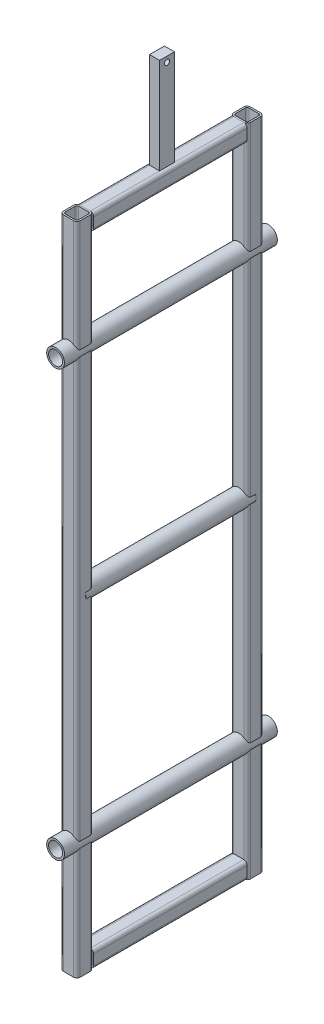
SolidWorks part; units mm, degrees
ref_plane "Front Plane" through (0, 0, 0) normal (1, 0, 0) x (0, 1, 0)
ref_plane "Top Plane" through (0, 0, 0) normal (0, 0, 1) x (0, 1, 0)
ref_plane "Right Plane" through (0, 0, 0) normal (0, 1, 0) x (-1, 0, 0)
sketch "Sketch1" plane through (0, 0, 0) normal (1, 0, 0) x (0, 1, 0)
  line L0 (-254, 254) -> (-254, -254) construction
  line L1 (-482.6, 254) -> (482.6, 254) construction
  line L2 (-482.6, 254) -> (-482.6, -254) construction
  line L3 (-482.6, -254) -> (482.6, -254) construction
  line L4 (482.6, 254) -> (482.6, -254) construction
  line L5 (-482.6, 254) -> (482.6, -254) construction
  line L6 (-482.6, -254) -> (482.6, 254) construction
  line L11 (-254, 133.6842) -> (254, -133.6842) construction
  line L13 (254, 254) -> (254, -254) construction
  point P0 (0, 0)
  point P6 (0, 0)
  dimension "D1" = 965.2
  dimension "D2" = 508
  dimension "D3" = 254
  dimension "D4" = 508
sketch3d "3DSketch1"
  line L7 (0, 0, 101.6) -> (0, 0, -101.6)
  line L8 (0, -381, 101.6) -> (0, 381, 101.6)
  line L9 (0, -254, 127) -> (0, -254, -127)
  line L10 (0, -254, 254) -> (0, -254, -254) construction
  line L11 (0, -381, 101.6) -> (0, -381, -101.6)
  line L12 (0, -381, -101.6) -> (0, 381, -101.6)
  line L13 (0, 381, 101.6) -> (0, 381, -101.6)
  line L14 (0, -381, 101.6) -> (0, 381, -101.6) construction
  line L15 (0, -381, -101.6) -> (0, 381, 101.6) construction
  line L16 (0, 254, 127) -> (0, 254, -127)
  line L17 (0, 254, 254) -> (0, 254, -254) construction
  point P0 (0, 0, 0)
  point P8 (0, 0, 0)
  dimension "D1" = 25.4
  dimension "D3" = 25.4
  dimension "D2" = 762
  dimension "D4" = 25.4
  dimension "D5" = 25.4
  dimension "D6" = 203.2
ref_plane "Plane2" through (0, -381, 101.6) normal (0, 0, -1) x (1, 0, 0)
ref_plane "Plane4" through (0, -381, 101.6) normal (0, 1, 0) x (1, 0, 0)
ref_plane "Plane5" through (0, -381, 101.6) normal (0, 0, -1) x (1, 0, 0)
ref_plane "Plane6" through (0, -381, 101.6) normal (0, 0, -1) x (1, 0, 0)
ref_plane "Plane7" through (0, -381, -101.6) normal (0, 1, 0) x (1, 0, 0)
ref_plane "Plane8" through (0, -381, 101.6) normal (0, 0, -1) x (1, 0, 0)
ref_plane "Plane9" through (0, -381, 101.6) normal (0, 0, -1) x (1, 0, 0)
ref_plane "Plane10" through (0, -381, 101.6) normal (0, 0, -1) x (1, 0, 0)
ref_plane "Plane11" through (0, -381, -101.6) normal (0, 1, 0) x (1, 0, 0)
ref_plane "Plane12" through (0, -381, 101.6) normal (0, 0, -1) x (1, 0, 0)
other "Pipe 21.3 X 2.3(1)"
ref_plane "Plane15" through (0, 0, 101.6) normal (0, 0, -1) x (1, 0, 0)
sketch "Sketch136" plane through (0, 0, 101.6) normal (0, 0, -1) x (1, 0, 0)
  circle A0 centre (0, 0) radius 8.35
  circle A1 centre (0, 0) radius 10.65
  point P3 (0, 10.65)
  point P5 (-10.65, 0)
  point P6 (0, -10.65)
  point P7 (10.65, 0)
  point P8 (0, 0)
  dimension "In_dia" = 16.7
  dimension "Out_dia" = 21.3
other "Square tube 20 X 20 X 2(7)"
ref_plane "Plane17" through (0, -381, -101.6) normal (0, 1, 0) x (1, 0, 0)
sketch "Sketch141" plane through (0, -381, -101.6) normal (0, 1, 0) x (1, 0, 0)
  line L0 (-6, -8) -> (6, -8)
  line L1 (-8, -6) -> (-8, 6)
  line L2 (6, 8) -> (-6, 8)
  line L3 (8, 6) -> (8, -6)
  line L4 (-6, -10) -> (6, -10)
  line L5 (-10, -6) -> (-10, 6)
  line L6 (6, 10) -> (-6, 10)
  line L7 (10, 6) -> (10, -6)
  arc A0 (10, 6) -> (6, 10) centre (6, 6) ccw
  arc A1 (6, -10) -> (10, -6) centre (6, -6) ccw
  arc A2 (-10, -6) -> (-6, -10) centre (-6, -6) ccw
  arc A3 (-6, 10) -> (-10, 6) centre (-6, 6) ccw
  arc A4 (-6, 8) -> (-8, 6) centre (-6, 6) ccw
  arc A5 (8, 6) -> (6, 8) centre (6, 6) ccw
  arc A6 (6, -8) -> (8, -6) centre (6, -6) ccw
  arc A7 (-8, -6) -> (-6, -8) centre (-6, -6) ccw
  point P0 (-10, 0)
  point P1 (10, 0)
  point P2 (0, 10)
  point P3 (0, -10)
  point P4 (0, 0)
  point P5 (-10, -10)
  point P6 (10, -10)
  point P7 (10, 10)
  point P8 (-10, 10)
  point P33 (0, 0)
  dimension "D1" = 4
  dimension "Thickness" = 2
  dimension "V_leg" = 20
sketch "Sketch143" plane through (0, 0, -127) normal (0, 0, -1) x (1, 0, 0)
  circle A0 centre (0, 254) radius 8.35
  circle A1 centre (0, -254) radius 8.35
extrude "Cut-Extrude1" cut sketch "Sketch143" against normal through all
sketch "Sketch144" plane through (0, 391, 0) normal (0, 1, 0) x (-1, 0, 0)
  line L0 (6, -91.6) -> (6, 91.6) construction
  line L1 (-6, 8.89) -> (6, 8.89)
  line L2 (-6, 8.89) -> (-6, -8.89)
  line L3 (-6, -8.89) -> (6, -8.89)
  line L4 (6, 8.89) -> (6, -8.89)
  line L5 (-6, 8.89) -> (6, -8.89) construction
  line L6 (-6, -8.89) -> (6, 8.89) construction
  point P0 (0, 0)
  dimension "D1" = 17.78
extrude "Boss-Extrude1" add sketch "Sketch144" along normal blind 114.3 separate body
sketch "Sketch145" plane through (6, 0, 0) normal (1, 0, 0) x (0, 1, 0)
  line L0 (505.3, -8.89) -> (391, -8.89) construction
  line L1 (505.3, 8.89) -> (492.6, 8.89) construction
  line L2 (505.3, 8.89) -> (505.3, -8.89) construction
  line L3 (505.3, -8.89) -> (492.6, -8.89) construction
  line L4 (492.6, 8.89) -> (492.6, -8.89) construction
  line L5 (498.95, 8.89) -> (498.95, -8.89) construction
  circle A0 centre (498.95, 0) radius 3.175
  dimension "D2" = 6.35
  dimension "D1" = 12.7
extrude "Cut-Extrude2" cut sketch "Sketch145" against normal through all
